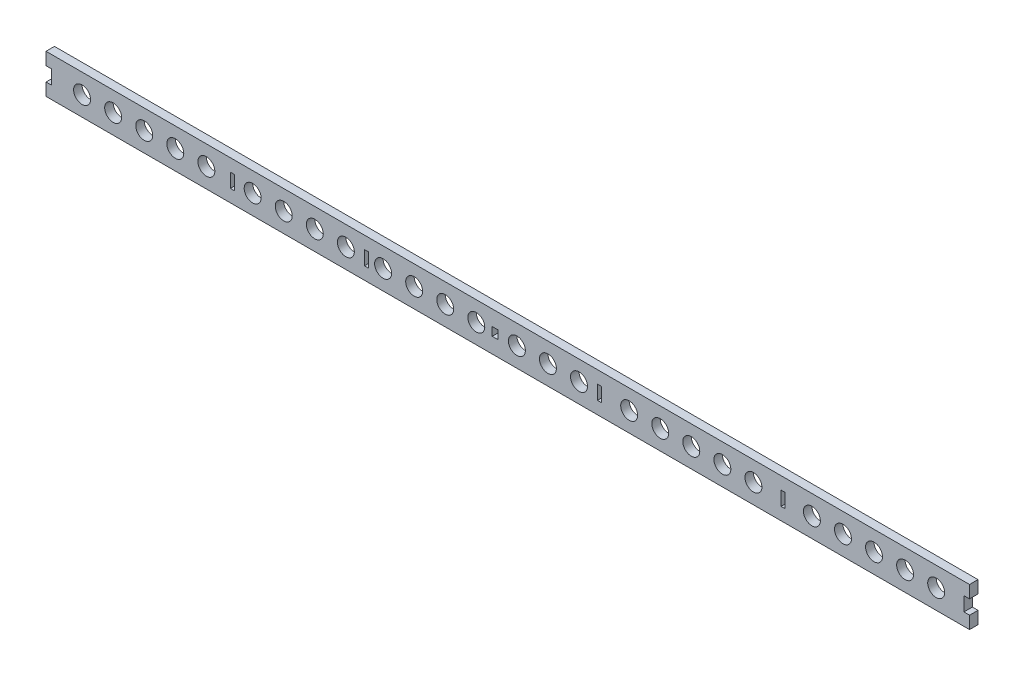
SolidWorks part; units mm, degrees
ref_plane "前视基准面" through (0, 0, 0) normal (0, 0, 1) x (1, 0, 0)
ref_plane "上视基准面" through (0, 0, 0) normal (0, 1, 0) x (1, 0, 0)
ref_plane "右视基准面" through (0, 0, 0) normal (1, 0, 0) x (0, 0, -1)
sketch "Model" plane through (0, 0, 0) normal (0, 0, 1) x (1, 0, 0)
  line L0 (13.8513, 22.7889) -> (13.8513, 18.3673)
  line L1 (13.8513, 13.3673) -> (13.8513, 8.9457)
  line L2 (340.8513, 22.7889) -> (340.8513, 18.3673)
  line L3 (340.8513, 13.3673) -> (338.8513, 13.3673)
  line L4 (338.8513, 13.3673) -> (338.8513, 18.3673)
  line L5 (338.8513, 18.3673) -> (340.8513, 18.3673)
  line L6 (15.8513, 18.3673) -> (15.8513, 13.3673)
  line L7 (15.8513, 13.3673) -> (13.8513, 13.3673)
  line L8 (13.8513, 18.3673) -> (15.8513, 18.3673)
  line L9 (79.1013, 18.3673) -> (80.6013, 18.3673)
  line L10 (80.6013, 18.3673) -> (80.6013, 13.3673)
  line L11 (80.6013, 13.3673) -> (79.1013, 13.3673)
  line L12 (79.1013, 13.3673) -> (79.1013, 18.3673)
  line L13 (209.1013, 18.3673) -> (210.6013, 18.3673)
  line L14 (210.6013, 18.3673) -> (210.6013, 13.3673)
  line L15 (210.6013, 13.3673) -> (209.1013, 13.3673)
  line L16 (209.1013, 13.3673) -> (209.1013, 18.3673)
  line L17 (274.1013, 18.3673) -> (275.6013, 18.3673)
  line L18 (275.6013, 18.3673) -> (275.6013, 13.3673)
  line L19 (275.6013, 13.3673) -> (274.1013, 13.3673)
  line L20 (274.1013, 13.3673) -> (274.1013, 18.3673)
  line L21 (173.8513, 17.3783) -> (173.8513, 14.3783)
  line L22 (173.8513, 14.3783) -> (171.8513, 14.3783)
  line L23 (171.8513, 14.3783) -> (171.8513, 17.3783)
  line L24 (171.8513, 17.3783) -> (173.8513, 17.3783)
  line L25 (128.1013, 18.3673) -> (128.1013, 13.3673)
  line L26 (128.1013, 13.3673) -> (126.6013, 13.3673)
  line L27 (126.6013, 13.3673) -> (126.6013, 18.3673)
  line L28 (126.6013, 18.3673) -> (128.1013, 18.3673)
  line L29 (29.8229, 8.9457) -> (13.8513, 8.9457)
  line L30 (29.825, 22.7889) -> (13.8513, 22.7889)
  line L31 (340.8513, 13.3673) -> (340.8513, 8.9457)
  line L32 (340.8513, 22.7889) -> (29.825, 22.7889)
  line L33 (29.8229, 8.9457) -> (340.8513, 8.9457)
  circle A0 centre (26.6312, 15.8673) radius 3
  circle A2 centre (37.6312, 15.8673) radius 3
  circle A3 centre (48.6312, 15.8673) radius 3
  circle A4 centre (48.6312, 15.8673) radius 3
  circle A5 centre (59.6312, 15.8673) radius 3
  circle A6 centre (59.6312, 15.8673) radius 3
  circle A7 centre (70.6312, 15.8673) radius 3
  circle A8 centre (87.0263, 15.8673) radius 3
  circle A9 centre (98.0263, 15.8673) radius 3
  circle A10 centre (98.0263, 15.8673) radius 3
  circle A11 centre (109.0263, 15.8673) radius 3
  circle A12 centre (109.0263, 15.8673) radius 3
  circle A13 centre (120.0263, 15.8673) radius 3
  circle A14 centre (120.0263, 15.8673) radius 3
  circle A15 centre (133.2054, 15.8673) radius 3
  circle A16 centre (144.2054, 15.8673) radius 3
  circle A17 centre (144.2054, 15.8673) radius 3
  circle A18 centre (155.2054, 15.8673) radius 3
  circle A19 centre (155.2054, 15.8673) radius 3
  circle A20 centre (166.2054, 15.8673) radius 3
  circle A21 centre (166.2054, 15.8673) radius 3
  circle A22 centre (180.5756, 15.8673) radius 3
  circle A23 centre (191.5756, 15.8673) radius 3
  circle A24 centre (191.5756, 15.8673) radius 3
  circle A25 centre (202.5756, 15.8673) radius 3
  circle A26 centre (202.5756, 15.8673) radius 3
  circle A27 centre (220.3356, 15.8673) radius 3
  circle A28 centre (231.3356, 15.8673) radius 3
  circle A29 centre (231.3356, 15.8673) radius 3
  circle A30 centre (242.3356, 15.8673) radius 3
  circle A31 centre (242.3356, 15.8673) radius 3
  circle A32 centre (253.3356, 15.8673) radius 3
  circle A33 centre (253.3356, 15.8673) radius 3
  circle A34 centre (264.3356, 15.8673) radius 3
  circle A35 centre (285.0403, 15.8673) radius 3
  circle A36 centre (296.0403, 15.8673) radius 3
  circle A37 centre (296.0403, 15.8673) radius 3
  circle A38 centre (307.0403, 15.8673) radius 3
  circle A39 centre (307.0403, 15.8673) radius 3
  circle A40 centre (318.0403, 15.8673) radius 3
  circle A41 centre (318.0403, 15.8673) radius 3
  circle A42 centre (329.0403, 15.8673) radius 3
extrude "凸台-拉伸1" add sketch "Model" along normal blind 3 contours L29 L33 L31 L3 L4 L5 L2 L32 L30 L0 L8 L6 L7 L1 A42 A40 A38 A36 A35 A34 A32 A30 A28 A27 A25 A23 A22 A20 A18 A16 A15 A13
